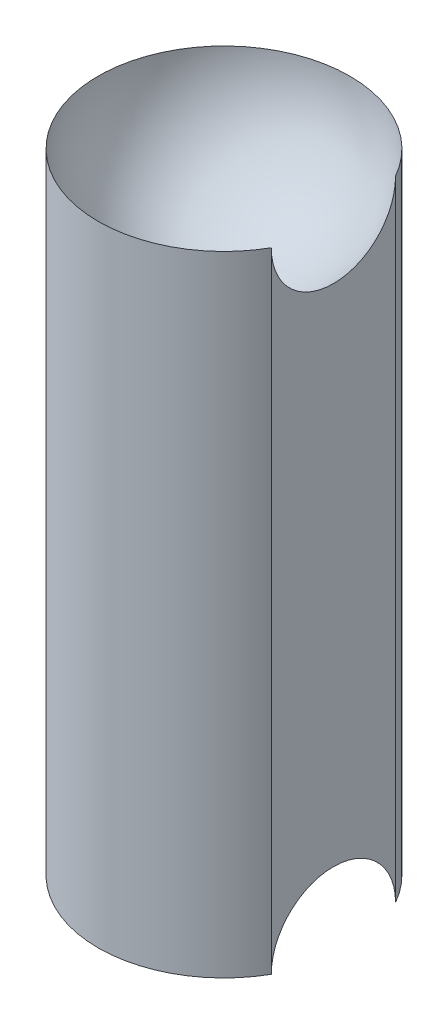
SolidWorks part; units mm, degrees
ref_plane "Front Plane" through (0, 0, 0) normal (0, 0, 1) x (1, 0, 0)
ref_plane "Top Plane" through (0, 0, 0) normal (0, 1, 0) x (1, 0, 0)
ref_plane "Right Plane" through (0, 0, 0) normal (1, 0, 0) x (0, 0, -1)
sketch "Sketch1" plane through (0, 0, 0) normal (0, 1, 0) x (1, 0, 0)
  circle A0 centre (0, 0) radius 50
  dimension "D1" = 100
extrude "Boss-Extrude1" add sketch "Sketch1" along normal blind 250
ref_plane "Plane1" through (0, 125, 0) normal (0, 1, 0) x (1, 0, 0)
sketch "Sketch2" plane through (0, 0, 0) normal (0, 0, 1) x (1, 0, 0)
  line L0 (50, 250) -> (-50, 250) construction
  line L2 (0, 250) -> (0, 0) construction
  line L3 (0, 300) -> (0, 200)
  arc A0 (0, 200) -> (0, 300) centre (0, 250) ccw
revolve "Cut-Revolve1" cut sketch "Sketch2" angle 360 about L3
mirror "Mirror2" about plane through (0, 125, 0) normal (0, 1, 0) of "Cut-Revolve1"
sketch "Sketch3" plane through (0, 0, 0) normal (0, 0, 1) x (1, 0, 0)
  line L1 (50.9969, 255.9815) -> (43.4816, 255.9815)
  line L2 (50.9969, 255.9815) -> (50.9969, -6.6973)
  line L3 (50.9969, -6.6973) -> (43.4816, -6.6973)
  line L4 (43.4816, 255.9815) -> (43.4816, -6.6973)
  dimension "D1" = 262.6788
  dimension "D2" = 7.5153
extrude "Cut-Extrude1" cut sketch "Sketch3" against normal through all both and the other way through all
